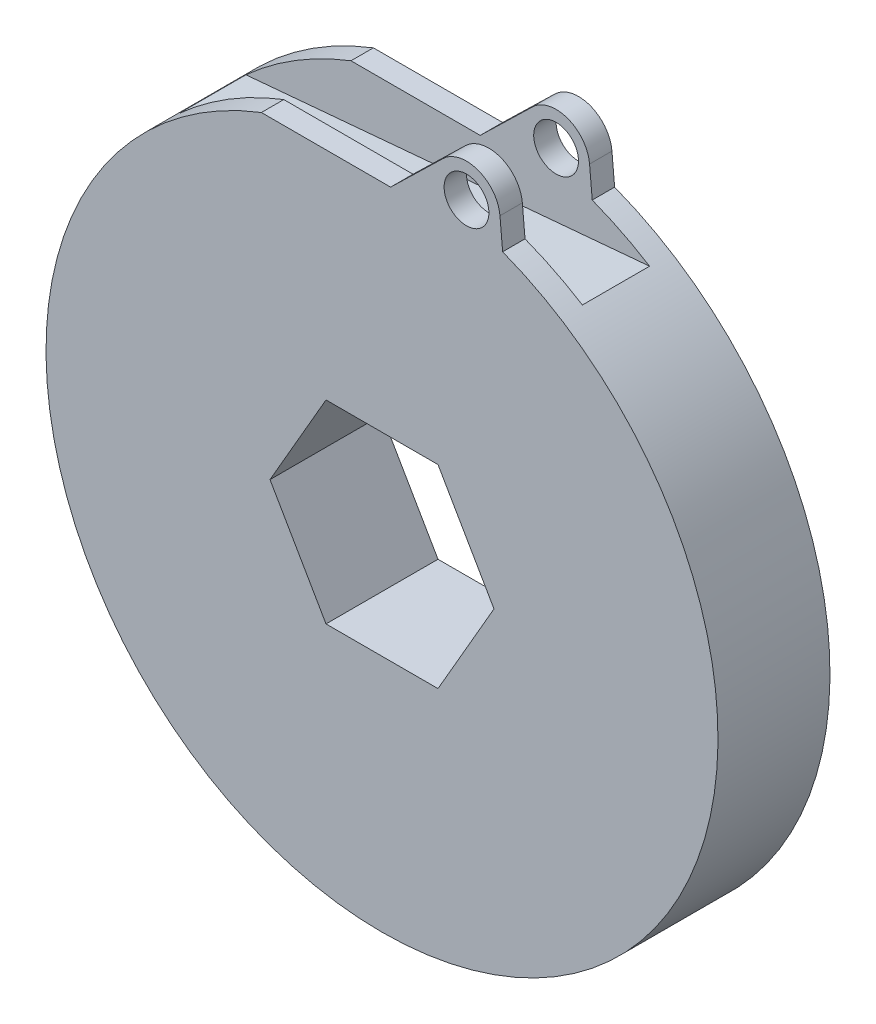
SolidWorks part; units mm, degrees
material "3003-H16"
ref_plane "前视基准面" through (0, 0, 0) normal (0, 0, 1) x (1, 0, 0)
ref_plane "上视基准面" through (0, 0, 0) normal (0, 1, 0) x (1, 0, 0)
ref_plane "右视基准面" through (0, 0, 0) normal (1, 0, 0) x (0, 0, -1)
sketch "草图1" plane through (0, 0, 0) normal (0, 0, 1) x (1, 0, 0)
  circle A0 centre (0, 0) radius 15
  dimension "D1" = 30
extrude "凸台-拉伸1" add sketch "草图1" along normal blind 5
sketch "草图2" plane through (0, 0, 5) normal (0, 0, 1) x (1, 0, 0)
  line L7 (-2.5, -4.3301) -> (2.5, -4.3301)
  line L8 (2.5, -4.3301) -> (5, 0)
  line L9 (5, 0) -> (2.5, 4.3301)
  line L10 (2.5, 4.3301) -> (-2.5, 4.3301)
  line L11 (-2.5, 4.3301) -> (-5, 0)
  line L12 (-5, 0) -> (-2.5, -4.3301)
  circle A0 centre (0, 0) radius 5 construction
  dimension "D1" = 10
extrude "切除-拉伸1" cut sketch "草图2" against normal blind 30
sketch "草图3" plane through (0, 0, 5) normal (0, 0, 1) x (1, 0, 0)
  line L0 (-8.5866, 14) -> (9.1238, 14)
  line L1 (-8.5866, 14) -> (-0.9515, 18.6752)
  line L2 (-0.9515, 18.6752) -> (9.1238, 14)
  dimension "D1" = 14
extrude "切除-拉伸2" cut sketch "草图3" against normal blind 60
sketch "草图4" plane through (0, 0, 5) normal (0, 0, 1) x (1, 0, 0)
  line L0 (5.3852, 14) -> (5.266, 15.3336)
  line L1 (2.7264, 16.2756) -> (0.3852, 14)
  line L2 (-5.3852, 14) -> (5.3852, 14) construction
  line L3 (0.3852, 14) -> (5.3852, 14)
  arc A0 (5.266, 15.3336) -> (2.7264, 16.2756) centre (3.7719, 15.2) ccw
  circle A1 centre (3.7719, 15.2) radius 1
  dimension "D1" = 3
  dimension "D4" = 2
  dimension "D2" = 5
  dimension "D3" = 1.2
extrude "凸台-拉伸2" add sketch "草图4" against normal up to surface (5 mm away) up to face at (0, 0, 0)
sketch "草图5" plane through (6.584, 0.5886, 0) normal (0.996, 0.089, 0) x (0, 0, -1)
  line L0 (0, 13.4649) -> (-5, 13.4649) construction
  line L1 (-4, 18.5054) -> (-1, 18.5054)
  line L2 (-4, 18.5054) -> (-4, 13.4649)
  line L3 (-4, 13.4649) -> (-1, 13.4649)
  line L4 (-1, 18.5054) -> (-1, 13.4649)
  line L5 (-5, 13.4649) -> (-5, 14.8038) construction
  line L6 (0, 14.8038) -> (0, 16.3038) construction
  dimension "D1" = 5.0405
  dimension "D2" = 1
  dimension "D3" = 1
extrude "切除-拉伸3" cut sketch "草图5" against normal through all
sketch "草图6" plane through (6.584, 0.5886, 0) normal (0.996, 0.089, 0) x (0, 0, -1)
  line L1 (-4, 13.4649) -> (-1, 13.4649)
  line L2 (-4, 13.4649) -> (-4, 11.9649)
  line L3 (-4, 11.9649) -> (-1, 11.9649)
  line L4 (-1, 13.4649) -> (-1, 11.9649)
  dimension "D1" = 1.5
extrude "切除-拉伸4" cut sketch "草图6" against normal through all both and the other way through all
